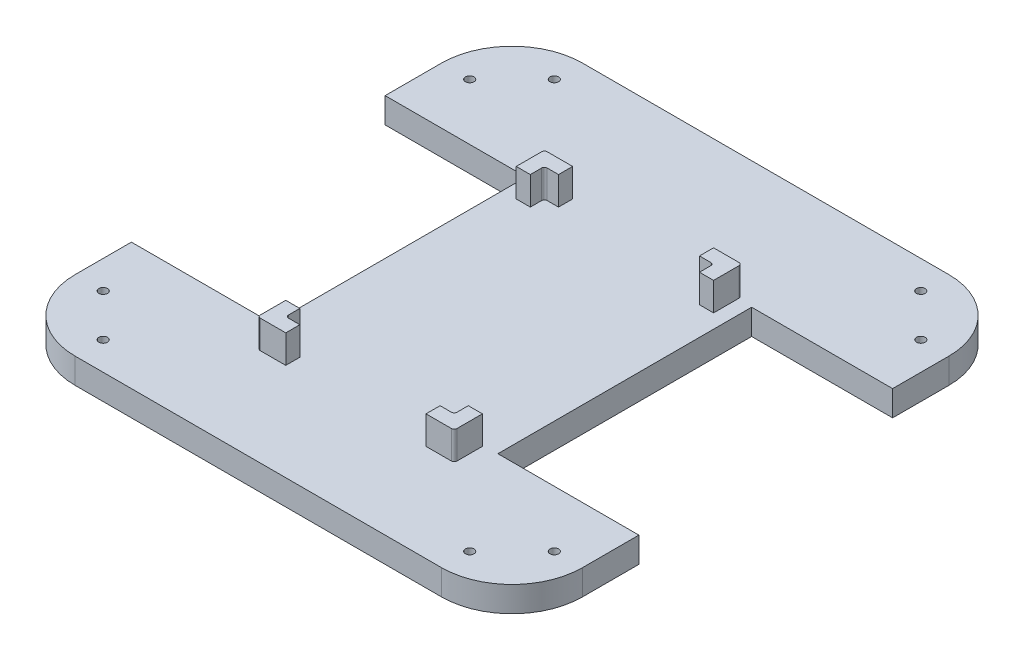
SolidWorks part; units mm, degrees
ref_plane "Front Plane" through (0, 0, 0) normal (0, 0, 1) x (1, 0, 0)
ref_plane "Top Plane" through (0, 0, 0) normal (0, 1, 0) x (1, 0, 0)
ref_plane "Right Plane" through (0, 0, 0) normal (1, 0, 0) x (0, 0, -1)
sketch "Sketch1" plane through (0, 0, 0) normal (0, 1, 0) x (1, 0, 0)
  line L1 (-65, -90) -> (65, -90)
  line L2 (-90, -65) -> (-90, 65)
  line L3 (-65, 90) -> (65, 90)
  line L4 (90, -65) -> (90, 65)
  arc A0 (-90, 65) -> (-65, 90) centre (-65, 65) cw
  arc A1 (65, 90) -> (90, 65) centre (65, 65) cw
  arc A2 (90, -65) -> (65, -90) centre (65, -65) cw
  arc A3 (-65, -90) -> (-90, -65) centre (-65, -65) cw
  point P4 (-90, 0)
  point P6 (0, 90)
  dimension "D3" = 25
  dimension "D1" = 180
  dimension "D2" = 180
extrude "Plate" add sketch "Sketch1" along normal blind 9
sketch "Sketch3" plane through (0, 9, 0) normal (0, 1, 0) x (1, 0, 0)
  line L0 (-65, 90) -> (-65, -90) construction
  line L1 (65, 90) -> (65, -90) construction
  line L2 (-90, 65) -> (90, 65) construction
  line L3 (-90, -65) -> (90, -65) construction
  circle A0 centre (-65, 80) radius 1.525
  circle A1 centre (-80, 65) radius 1.525
  circle A2 centre (80, 65) radius 1.525
  circle A3 centre (80, -65) radius 1.525
  circle A4 centre (65, 80) radius 1.525
  circle A5 centre (65, -80) radius 1.525
  circle A6 centre (-65, -80) radius 1.525
  circle A7 centre (-80, -65) radius 1.525
  dimension "D1" = 3.05
  dimension "D2" = 15
  dimension "D3" = 15
  dimension "D4" = 15
  dimension "D5" = 15
  dimension "D6" = 15
  dimension "D7" = 15
  dimension "D8" = 15
  dimension "D9" = 15
extrude "Hex Holes" cut sketch "Sketch3" against normal through all
sketch "Sketch4" plane through (0, 9, 0) normal (0, 1, 0) x (1, 0, 0)
  line L0 (0, 90) -> (0, -90) construction
  line L1 (-65, 90) -> (65, 90) construction
  line L2 (-65, -90) -> (65, -90) construction
  line L3 (-30, 36.5) -> (-30, 41.5)
  line L4 (-29.5, 41) -> (29.5, 41) construction
  line L5 (-29.5, 41) -> (-29.5, -50) construction
  line L6 (-29.5, -50) -> (29.5, -50) construction
  line L7 (29.5, 41) -> (29.5, -50) construction
  line L8 (-30, 41.5) -> (-25, 41.5)
  line L9 (-25, 41.5) -> (-25, 46.5)
  line L10 (-25, 46.5) -> (-35, 46.5)
  line L11 (-35, 46.5) -> (-35, 36.5)
  line L12 (-35, 36.5) -> (-30, 36.5)
  line L13 (25, 46.5) -> (35, 46.5)
  line L14 (35, 46.5) -> (35, 36.5)
  line L15 (35, 36.5) -> (30, 36.5)
  line L16 (30, 36.5) -> (30, 41.5)
  line L17 (30, 41.5) -> (25, 41.5)
  line L18 (25, 41.5) -> (25, 46.5)
  line L19 (-34.75, -45.5) -> (-34.75, -55.5)
  line L20 (-34.75, -55.5) -> (-24.75, -55.5)
  line L21 (-24.75, -55.5) -> (-24.75, -50.5)
  line L22 (-24.75, -50.5) -> (-29.75, -50.5)
  line L23 (-29.75, -50.5) -> (-29.75, -45.5)
  line L24 (-29.75, -45.5) -> (-34.75, -45.5)
  line L25 (25, -50.5) -> (25, -55.5)
  line L26 (25, -55.5) -> (35, -55.5)
  line L27 (35, -55.5) -> (35, -45.5)
  line L28 (35, -45.5) -> (30, -45.5)
  line L29 (30, -45.5) -> (30, -50.5)
  line L30 (30, -50.5) -> (25, -50.5)
  point P10 (0, 41)
  point P25 (-35, 41.5)
  dimension "D1" = 91
  dimension "D2" = 59
  dimension "D3" = 40
  dimension "D4" = 0.5
  dimension "D5" = 0.5
  dimension "D6" = 5
  dimension "D7" = 0.5
  dimension "D8" = 0.5
  dimension "D9" = 0.5
  dimension "D10" = 0.5
  dimension "D11" = 0.5
extrude "Raspberry Pi Holder" add sketch "Sketch4" along normal blind 10
fillet "Fillet1" radius 1 8 edges at (-35, 14, -46.5) (-30, 14, -41.5) (-29.75, 14, 50.5) (-34.75, 14, 55.5) (30, 14, 50.5) (35, 14, 55.5) (35, 14, -46.5) (30, 14, -41.5)
sketch "Sketch5" plane through (0, 9, 0) normal (0, 1, 0) x (1, 0, 0)
  line L0 (-90, -65) -> (-90, 65) construction
  line L1 (-90, 45) -> (-40, 45)
  line L2 (-90, 45) -> (-90, -45)
  line L3 (-90, -45) -> (-40, -45)
  line L4 (-40, 45) -> (-40, -45)
  line L5 (90, -65) -> (90, 65) construction
  line L6 (90, 45) -> (40, 45)
  line L7 (90, 45) -> (90, -45)
  line L8 (90, -45) -> (40, -45)
  line L9 (40, 45) -> (40, -45)
  point P12 (-90, 0)
  point P14 (90, 0)
  dimension "D1" = 90
  dimension "D2" = 50
extrude "Cut-Extrude1" cut sketch "Sketch5" against normal through all
